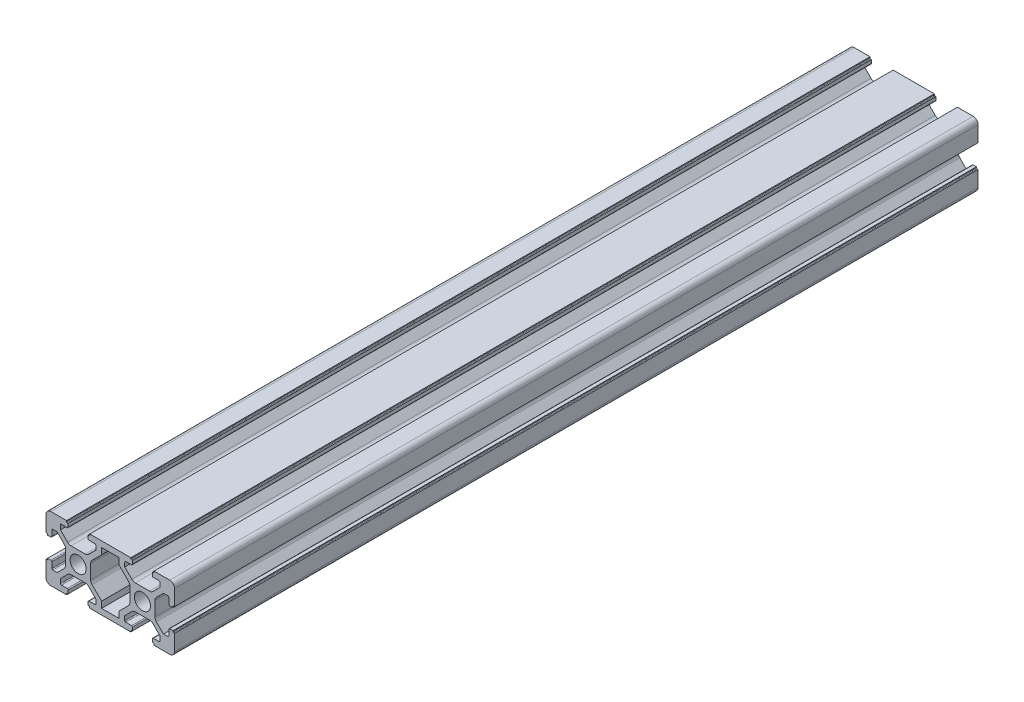
SolidWorks part; units mm, degrees
ref_plane "前视基准面" through (0, 0, 0) normal (0, 0, 1) x (1, 0, 0)
ref_plane "上视基准面" through (0, 0, 0) normal (0, 1, 0) x (1, 0, 0)
ref_plane "右视基准面" through (0, 0, 0) normal (1, 0, 0) x (0, 0, -1)
sketch "草图1" plane through (0, 0, 0) normal (0, 0, 1) x (1, 0, 0)
  line L0 (-1.9716, -6.6942) -> (-4.9322, -3.7335)
  line L1 (-5.3716, -2.6729) -> (-5.3716, 1.7645)
  line L2 (-4.9322, 2.8251) -> (-1.9716, 5.7858)
  line L3 (-0.7716, 9.5458) -> (-5.6716, 9.5458)
  line L4 (-5.6716, 9.5458) -> (-5.6716, 9.2458)
  line L5 (-5.8716, 9.0458) -> (-6.1716, 9.0458)
  line L6 (-6.1716, 9.0458) -> (-6.1716, 8.0458)
  line L7 (-5.8716, 7.7458) -> (-4.0716, 7.7458)
  line L8 (-3.7716, 7.4458) -> (-3.7716, 6.1058)
  line L9 (-3.7716, 6.1058) -> (-5.9922, 3.8851)
  line L10 (-7.0529, 3.4458) -> (-11.4903, 3.4458)
  line L11 (-12.5509, 3.8851) -> (-14.7716, 6.1058)
  line L12 (-14.7716, 6.1058) -> (-14.7716, 7.4458)
  line L13 (-14.4716, 7.7458) -> (-12.6716, 7.7458)
  line L14 (-12.3716, 8.0458) -> (-12.3716, 9.0458)
  line L15 (-12.3716, 9.0458) -> (-12.6716, 9.0458)
  line L16 (-12.8716, 9.2458) -> (-12.8716, 9.5458)
  line L17 (-12.8716, 9.5458) -> (-17.7716, 9.5458)
  line L18 (-19.2716, 8.0458) -> (-19.2716, 3.1458)
  line L19 (-19.2716, 3.1458) -> (-18.9716, 3.1458)
  line L20 (-18.7716, 2.9458) -> (-18.7716, 2.6458)
  line L21 (-18.7716, 2.6458) -> (-17.7716, 2.6458)
  line L22 (-17.4716, 2.9458) -> (-17.4716, 4.7458)
  line L23 (-17.1716, 5.0458) -> (-15.8316, 5.0458)
  line L24 (-15.8316, 5.0458) -> (-13.6109, 2.8251)
  line L25 (-13.1716, 1.7645) -> (-13.1716, -2.6729)
  line L26 (-13.6109, -3.7335) -> (-15.8316, -5.9542)
  line L27 (-15.8316, -5.9542) -> (-17.1716, -5.9542)
  line L28 (-17.4716, -5.6542) -> (-17.4716, -3.8542)
  line L29 (-17.7716, -3.5542) -> (-18.7716, -3.5542)
  line L30 (-18.7716, -3.5542) -> (-18.7716, -3.8542)
  line L31 (-18.9716, -4.0542) -> (-19.2716, -4.0542)
  line L32 (-19.2716, -4.0542) -> (-19.2716, -8.9542)
  line L33 (-17.7716, -10.4542) -> (-12.8716, -10.4542)
  line L34 (-12.8716, -10.4542) -> (-12.8716, -10.1542)
  line L35 (-12.6716, -9.9542) -> (-12.3716, -9.9542)
  line L36 (-12.3716, -9.9542) -> (-12.3716, -8.9542)
  line L37 (-12.6716, -8.6542) -> (-14.4716, -8.6542)
  line L38 (-14.7716, -8.3542) -> (-14.7716, -7.0142)
  line L39 (-14.7716, -7.0142) -> (-12.5509, -4.7935)
  line L40 (-11.4903, -4.3542) -> (-7.0529, -4.3542)
  line L41 (-5.9922, -4.7935) -> (-3.7716, -7.0142)
  line L42 (-3.7716, -7.0142) -> (-3.7716, -8.3542)
  line L43 (-4.0716, -8.6542) -> (-5.8716, -8.6542)
  line L44 (-6.1716, -8.9542) -> (-6.1716, -9.9542)
  line L45 (-6.1716, -9.9542) -> (-5.8716, -9.9542)
  line L46 (-5.6716, -10.1542) -> (-5.6716, -10.4542)
  line L47 (-5.6716, -10.4542) -> (-0.7716, -10.4542)
  line L48 (-0.7716, -10.4542) -> (7.1284, -10.4542)
  line L49 (7.1284, -10.4542) -> (7.1284, -10.1542)
  line L50 (7.3284, -9.9542) -> (7.6284, -9.9542)
  line L51 (7.6284, -9.9542) -> (7.6284, -8.9542)
  line L52 (7.3284, -8.6542) -> (5.5284, -8.6542)
  line L53 (5.2284, -8.3542) -> (5.2284, -7.0142)
  line L54 (5.2284, -7.0142) -> (7.4491, -4.7935)
  line L55 (8.5097, -4.3542) -> (12.9471, -4.3542)
  line L56 (14.0078, -4.7935) -> (16.2284, -7.0142)
  line L57 (16.2284, -7.0142) -> (16.2284, -8.3542)
  line L58 (15.9284, -8.6542) -> (14.1284, -8.6542)
  line L59 (13.8284, -8.9542) -> (13.8284, -9.9542)
  line L60 (13.8284, -9.9542) -> (14.1284, -9.9542)
  line L61 (14.3284, -10.1542) -> (14.3284, -10.4542)
  line L62 (14.3284, -10.4542) -> (19.2284, -10.4542)
  line L63 (20.7284, -8.9542) -> (20.7284, -4.0542)
  line L64 (20.7284, -4.0542) -> (20.4284, -4.0542)
  line L65 (20.2284, -3.8542) -> (20.2284, -3.5542)
  line L66 (20.2284, -3.5542) -> (19.2284, -3.5542)
  line L67 (18.9284, -3.8542) -> (18.9284, -5.6542)
  line L68 (18.6284, -5.9542) -> (17.2884, -5.9542)
  line L69 (17.2884, -5.9542) -> (15.0678, -3.7335)
  line L70 (14.6284, -2.6729) -> (14.6284, 1.7645)
  line L71 (15.0678, 2.8251) -> (17.2884, 5.0458)
  line L72 (17.2884, 5.0458) -> (18.6284, 5.0458)
  line L73 (18.9284, 4.7458) -> (18.9284, 2.9458)
  line L74 (19.2284, 2.6458) -> (20.2284, 2.6458)
  line L75 (20.2284, 2.6458) -> (20.2284, 2.9458)
  line L76 (20.4284, 3.1458) -> (20.7284, 3.1458)
  line L77 (20.7284, 3.1458) -> (20.7284, 8.0458)
  line L78 (19.2284, 9.5458) -> (14.3284, 9.5458)
  line L79 (14.3284, 9.5458) -> (14.3284, 9.2458)
  line L80 (14.1284, 9.0458) -> (13.8284, 9.0458)
  line L81 (13.8284, 9.0458) -> (13.8284, 8.0458)
  line L82 (14.1284, 7.7458) -> (15.9284, 7.7458)
  line L83 (16.2284, 7.4458) -> (16.2284, 6.1058)
  line L84 (16.2284, 6.1058) -> (14.0078, 3.8851)
  line L85 (12.9471, 3.4458) -> (8.5097, 3.4458)
  line L86 (7.4491, 3.8851) -> (5.2284, 6.1058)
  line L87 (5.2284, 6.1058) -> (5.2284, 7.4458)
  line L88 (5.5284, 7.7458) -> (7.3284, 7.7458)
  line L89 (7.6284, 8.0458) -> (7.6284, 9.0458)
  line L90 (7.6284, 9.0458) -> (7.3284, 9.0458)
  line L91 (7.1284, 9.2458) -> (7.1284, 9.5458)
  line L92 (7.1284, 9.5458) -> (2.2284, 9.5458)
  line L93 (3.4284, 5.7858) -> (6.3891, 2.8251)
  line L94 (6.8284, 1.7645) -> (6.8284, -2.6729)
  line L95 (6.3891, -3.7335) -> (3.4284, -6.6942)
  line L96 (-0.7716, 9.5458) -> (2.2284, 9.5458)
  line L99 (-1.9716, 7.7458) -> (3.4284, 7.7458)
  line L100 (3.4284, 7.7458) -> (3.4284, 5.7858)
  line L101 (-1.9716, 7.7458) -> (-1.9716, 5.7858)
  line L102 (-1.9716, -8.6542) -> (3.4284, -8.6542)
  line L103 (3.4284, -8.6542) -> (3.4284, -6.6942)
  line L104 (-1.9716, -8.6542) -> (-1.9716, -6.6942)
  arc A1 (-5.3716, -2.6729) -> (-4.9322, -3.7335) centre (-3.8716, -2.6729) ccw
  arc A2 (-4.9322, 2.8251) -> (-5.3716, 1.7645) centre (-3.8716, 1.7645) ccw
  arc A3 (-5.8716, 9.0458) -> (-5.6716, 9.2458) centre (-5.8716, 9.2458) ccw
  arc A4 (-6.1716, 8.0458) -> (-5.8716, 7.7458) centre (-5.8716, 8.0458) ccw
  arc A5 (-3.7716, 7.4458) -> (-4.0716, 7.7458) centre (-4.0716, 7.4458) ccw
  arc A6 (-7.0529, 3.4458) -> (-5.9922, 3.8851) centre (-7.0529, 4.9458) ccw
  arc A7 (-12.5509, 3.8851) -> (-11.4903, 3.4458) centre (-11.4903, 4.9458) ccw
  arc A8 (-14.4716, 7.7458) -> (-14.7716, 7.4458) centre (-14.4716, 7.4458) ccw
  arc A9 (-12.6716, 7.7458) -> (-12.3716, 8.0458) centre (-12.6716, 8.0458) ccw
  arc A10 (-12.8716, 9.2458) -> (-12.6716, 9.0458) centre (-12.6716, 9.2458) ccw
  arc A11 (-17.7716, 9.5458) -> (-19.2716, 8.0458) centre (-17.7716, 8.0458) ccw
  arc A12 (-18.7716, 2.9458) -> (-18.9716, 3.1458) centre (-18.9716, 2.9458) ccw
  arc A13 (-17.7716, 2.6458) -> (-17.4716, 2.9458) centre (-17.7716, 2.9458) ccw
  arc A14 (-17.1716, 5.0458) -> (-17.4716, 4.7458) centre (-17.1716, 4.7458) ccw
  arc A15 (-13.1716, 1.7645) -> (-13.6109, 2.8251) centre (-14.6716, 1.7645) ccw
  arc A16 (-13.6109, -3.7335) -> (-13.1716, -2.6729) centre (-14.6716, -2.6729) ccw
  arc A17 (-17.4716, -5.6542) -> (-17.1716, -5.9542) centre (-17.1716, -5.6542) ccw
  arc A18 (-17.4716, -3.8542) -> (-17.7716, -3.5542) centre (-17.7716, -3.8542) ccw
  arc A19 (-18.9716, -4.0542) -> (-18.7716, -3.8542) centre (-18.9716, -3.8542) ccw
  arc A20 (-19.2716, -8.9542) -> (-17.7716, -10.4542) centre (-17.7716, -8.9542) ccw
  arc A21 (-12.6716, -9.9542) -> (-12.8716, -10.1542) centre (-12.6716, -10.1542) ccw
  arc A22 (-12.3716, -8.9542) -> (-12.6716, -8.6542) centre (-12.6716, -8.9542) ccw
  arc A23 (-14.7716, -8.3542) -> (-14.4716, -8.6542) centre (-14.4716, -8.3542) ccw
  arc A24 (-11.4903, -4.3542) -> (-12.5509, -4.7935) centre (-11.4903, -5.8542) ccw
  arc A25 (-5.9922, -4.7935) -> (-7.0529, -4.3542) centre (-7.0529, -5.8542) ccw
  arc A26 (-4.0716, -8.6542) -> (-3.7716, -8.3542) centre (-4.0716, -8.3542) ccw
  arc A27 (-5.8716, -8.6542) -> (-6.1716, -8.9542) centre (-5.8716, -8.9542) ccw
  arc A28 (-5.6716, -10.1542) -> (-5.8716, -9.9542) centre (-5.8716, -10.1542) ccw
  arc A29 (7.3284, -9.9542) -> (7.1284, -10.1542) centre (7.3284, -10.1542) ccw
  arc A30 (7.6284, -8.9542) -> (7.3284, -8.6542) centre (7.3284, -8.9542) ccw
  arc A31 (5.2284, -8.3542) -> (5.5284, -8.6542) centre (5.5284, -8.3542) ccw
  arc A32 (8.5097, -4.3542) -> (7.4491, -4.7935) centre (8.5097, -5.8542) ccw
  arc A33 (14.0078, -4.7935) -> (12.9471, -4.3542) centre (12.9471, -5.8542) ccw
  arc A34 (15.9284, -8.6542) -> (16.2284, -8.3542) centre (15.9284, -8.3542) ccw
  arc A35 (14.1284, -8.6542) -> (13.8284, -8.9542) centre (14.1284, -8.9542) ccw
  arc A36 (14.3284, -10.1542) -> (14.1284, -9.9542) centre (14.1284, -10.1542) ccw
  arc A37 (19.2284, -10.4542) -> (20.7284, -8.9542) centre (19.2284, -8.9542) ccw
  arc A38 (20.2284, -3.8542) -> (20.4284, -4.0542) centre (20.4284, -3.8542) ccw
  arc A39 (19.2284, -3.5542) -> (18.9284, -3.8542) centre (19.2284, -3.8542) ccw
  arc A40 (18.6284, -5.9542) -> (18.9284, -5.6542) centre (18.6284, -5.6542) ccw
  arc A41 (14.6284, -2.6729) -> (15.0678, -3.7335) centre (16.1284, -2.6729) ccw
  arc A42 (15.0678, 2.8251) -> (14.6284, 1.7645) centre (16.1284, 1.7645) ccw
  arc A43 (18.9284, 4.7458) -> (18.6284, 5.0458) centre (18.6284, 4.7458) ccw
  arc A44 (18.9284, 2.9458) -> (19.2284, 2.6458) centre (19.2284, 2.9458) ccw
  arc A45 (20.4284, 3.1458) -> (20.2284, 2.9458) centre (20.4284, 2.9458) ccw
  arc A46 (20.7284, 8.0458) -> (19.2284, 9.5458) centre (19.2284, 8.0458) ccw
  arc A47 (14.1284, 9.0458) -> (14.3284, 9.2458) centre (14.1284, 9.2458) ccw
  arc A48 (13.8284, 8.0458) -> (14.1284, 7.7458) centre (14.1284, 8.0458) ccw
  arc A49 (16.2284, 7.4458) -> (15.9284, 7.7458) centre (15.9284, 7.4458) ccw
  arc A50 (12.9471, 3.4458) -> (14.0078, 3.8851) centre (12.9471, 4.9458) ccw
  arc A51 (7.4491, 3.8851) -> (8.5097, 3.4458) centre (8.5097, 4.9458) ccw
  arc A52 (5.5284, 7.7458) -> (5.2284, 7.4458) centre (5.5284, 7.4458) ccw
  arc A53 (7.3284, 7.7458) -> (7.6284, 8.0458) centre (7.3284, 8.0458) ccw
  arc A54 (7.1284, 9.2458) -> (7.3284, 9.0458) centre (7.3284, 9.2458) ccw
  arc A55 (6.8284, 1.7645) -> (6.3891, 2.8251) centre (5.3284, 1.7645) ccw
  arc A56 (6.3891, -3.7335) -> (6.8284, -2.6729) centre (5.3284, -2.6729) ccw
  circle A58 centre (10.7284, -0.4542) radius 2.5
  circle A63 centre (-9.2716, -0.4542) radius 2.5
extrude "凸台-拉伸1" add sketch "草图1" along normal blind 250
